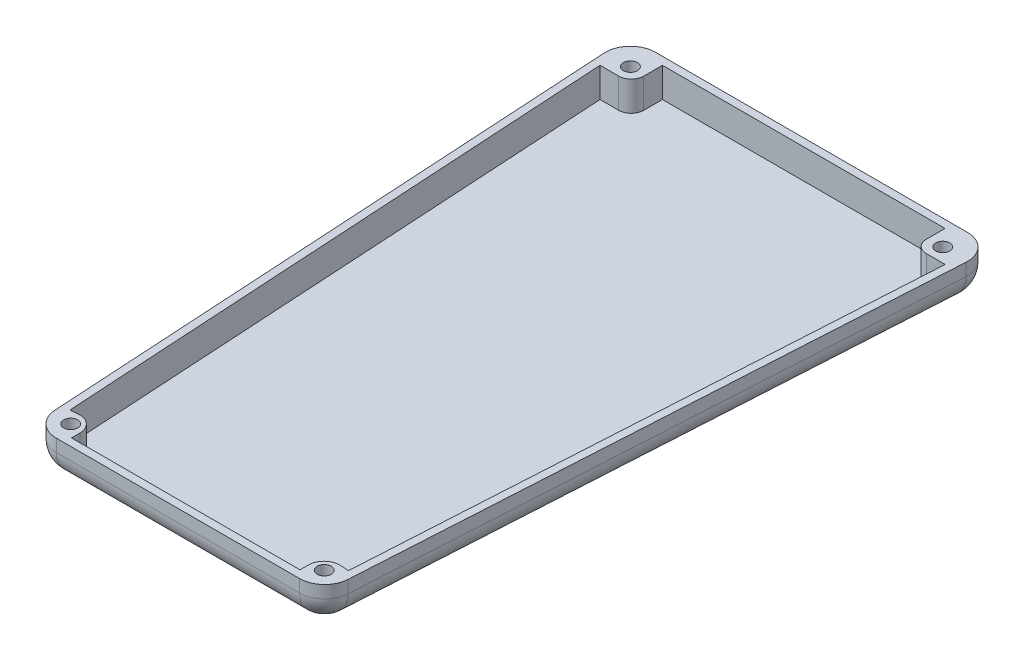
SolidWorks part; units mm, degrees
ref_plane "Front Plane" through (0, 0, 0) normal (0, 0, 1) x (1, 0, 0)
ref_plane "Top Plane" through (0, 0, 0) normal (0, 1, 0) x (1, 0, 0)
ref_plane "Right Plane" through (0, 0, 0) normal (1, 0, 0) x (0, 0, -1)
sketch "Sketch1" plane through (0, 76.7242, 0) normal (0, -1, 0) x (1, 0, 0)
  line L8 (110.2591, 82.3461) -> (10.2328, 82.3461) construction
  line L9 (110.2591, 82.3461) -> (10.2328, 82.3461)
  line L10 (21.3417, 285.3461) -> (99.2596, 285.3461) construction
  line L11 (2.2469, 90.8205) -> (13.3558, 277.8205) construction
  line L12 (107.2458, 277.8159) -> (118.2453, 90.8159) construction
  line L13 (21.3417, 285.3461) -> (99.2596, 285.3461)
  line L14 (2.2469, 90.8205) -> (13.3558, 277.8205)
  line L15 (107.2458, 277.8159) -> (118.2453, 90.8159)
  arc A0 (110.2591, 82.3461) -> (118.2453, 90.8159) centre (110.2591, 90.3461) ccw construction
  arc A1 (2.2469, 90.8205) -> (10.2328, 82.3461) centre (10.2328, 90.3461) ccw construction
  arc A2 (110.2591, 82.3461) -> (118.2453, 90.8159) centre (110.2591, 90.3461) ccw
  arc A3 (2.2469, 90.8205) -> (10.2328, 82.3461) centre (10.2328, 90.3461) ccw
  arc A4 (21.3417, 285.3461) -> (13.3558, 277.8205) centre (21.3417, 277.3461) ccw construction
  arc A5 (107.2458, 277.8159) -> (99.2596, 285.3461) centre (99.2596, 277.3461) ccw construction
  arc A6 (21.3417, 285.3461) -> (13.3558, 277.8205) centre (21.3417, 277.3461) ccw
  arc A7 (107.2458, 277.8159) -> (99.2596, 285.3461) centre (99.2596, 277.3461) ccw
extrude "Boss-Extrude1" add sketch "Sketch1" along normal blind 12
shell "Shell1" thickness 2.5
fillet "Fillet2" radius 8 8 edges at (116.0796, 64.7242, 84.8579) (60.2459, 64.7242, 82.3461) (4.4106, 64.7242, 84.8596) (7.8013, 64.7242, 184.3205) (15.8552, 64.7242, 283.1683) (60.3007, 64.7242, 285.3461) (104.7479, 64.7242, 283.1667) (112.7455, 64.7242, 184.3159)
sketch "Sketch5" plane through (0, 76.7242, 0) normal (0, 1, 0) x (1, 0, 0)
  line L0 (102.1959, -275.1575) -> (104.8885, -275.3159) construction
  line L1 (102.1959, -275.1575) -> (104.8885, -275.3159)
  line L2 (96.9023, -282.8461) -> (96.9023, -280.1489) construction
  line L3 (96.9023, -282.8461) -> (96.9023, -280.1489)
  line L4 (15.7117, -275.3205) -> (18.4011, -275.1608) construction
  line L5 (15.7117, -275.3205) -> (18.4011, -275.1608)
  line L6 (23.6976, -280.152) -> (23.6976, -282.8461) construction
  line L7 (23.6976, -280.152) -> (23.6976, -282.8461)
  line L8 (104.8885, -275.3159) -> (104.7501, -277.6691)
  line L9 (96.9023, -282.8461) -> (99.2596, -282.8461)
  line L10 (15.7117, -275.3205) -> (15.8514, -277.6723)
  line L11 (21.3417, -282.8461) -> (23.6976, -282.8461)
  line L12 (10.2328, -84.8461) -> (14.9904, -84.8461)
  line L13 (10.2328, -84.8461) -> (110.2591, -84.8461) construction
  line L14 (4.7425, -90.6723) -> (4.9904, -94.8461)
  line L15 (15.8514, -277.6723) -> (4.7425, -90.6723) construction
  line L16 (4.9904, -94.8461) -> (14.9904, -94.8461)
  line L17 (14.9904, -94.8461) -> (14.9904, -84.8461)
  line L18 (60.2459, -84.8461) -> (60.3007, -282.8461) construction
  line L19 (99.2596, -282.8461) -> (21.3417, -282.8461) construction
  line L20 (105.507, -94.8211) -> (105.5014, -84.8211)
  line L21 (115.507, -94.8156) -> (105.507, -94.8211)
  line L22 (115.7526, -90.6416) -> (115.507, -94.8156)
  line L23 (110.2591, -84.8185) -> (105.5014, -84.8211)
  arc A0 (102.1959, -275.1575) -> (96.9023, -280.1489) centre (101.9023, -280.1489) ccw construction
  arc A1 (102.1959, -275.1575) -> (96.9023, -280.1489) centre (101.9023, -280.1489) ccw
  arc A2 (23.6976, -280.152) -> (18.4011, -275.1608) centre (18.6976, -280.152) ccw construction
  arc A3 (23.6976, -280.152) -> (18.4011, -275.1608) centre (18.6976, -280.152) ccw
  circle A4 centre (10.2328, -90.3461) radius 1.5 construction
  circle A5 centre (10.2328, -90.3461) radius 1.5
  circle A6 centre (110.2591, -90.3461) radius 1.5 construction
  circle A7 centre (110.2591, -90.3461) radius 1.5
  circle A8 centre (100.9023, -279.0883) radius 1.5 construction
  circle A9 centre (100.9023, -279.0883) radius 1.5
  circle A10 centre (19.6976, -279.0908) radius 1.5 construction
  circle A11 centre (19.6976, -279.0908) radius 1.5
  arc A12 (99.2596, -282.8461) -> (104.7501, -277.6691) centre (99.2596, -277.3461) ccw construction
  arc A13 (99.2596, -282.8461) -> (104.7501, -277.6691) centre (99.2596, -277.3461) ccw
  arc A14 (15.8514, -277.6723) -> (21.3417, -282.8461) centre (21.3417, -277.3461) ccw construction
  arc A15 (15.8514, -277.6723) -> (21.3417, -282.8461) centre (21.3417, -277.3461) ccw
  arc A18 (10.2328, -84.8461) -> (4.7425, -90.6723) centre (10.2328, -90.3461) ccw construction
  arc A19 (10.2328, -84.8461) -> (4.7425, -90.6723) centre (10.2328, -90.3461) ccw
  arc A20 (110.2591, -84.8185) -> (115.7526, -90.6416) centre (110.2621, -90.3185) cw
  circle A21 centre (110.2621, -90.3185) radius 1.5
  line M6 (15.8514, -277.6723) -> (4.7425, -90.6723)
  line M9 (10.2328, -84.8461) -> (110.2591, -84.8461)
  arc M20 (4.7425, -90.6723) -> (10.2328, -84.8461) centre (10.2328, -90.3461) cw
  dimension "D1" = 10
  dimension "D2" = 10
extrude "Boss-Extrude3" add sketch "Sketch5" against normal up to surface (9.5 mm away) contours L16 L17 A5 M9 M20 M6 | A20 L22 L21 L20 L23 | A7 | A3 L5 L10 A15 L11 L7 | A11 | A1 L3 L9 A13 L8 L1 | A9
fillet "Fillet5" radius 4 2 edges at (14.9904, 71.9742, 94.8461) (105.507, 71.9742, 94.8211)
hole_wizard "CSK for M4 Countersunk Flat Head Screw1" positions "Sketch11" profile "Sketch12" countersink size "M4" standard "ISO"
sketch "Sketch11" plane through (0, 64.7242, 0) normal (0, -1, 0) x (-1, 0, 0)
  point P0 (-10.2328, -90.3461)
  point P3 (-110.2591, -90.3461)
sketch "Sketch12" plane through (10.2328, 64.7242, 90.3461) normal (1, 0, 0) x (0, 0, -1)
  line L0 (0, 0) -> (0, 13.3509)
  line L1 (0, 13.3509) -> (2.25, 11.999)
  line L2 (2.25, 11.999) -> (2.25, 2.45)
  line L3 (2.25, 2.45) -> (4.7, 0)
  line L5 (4.7, 0) -> (0, 0)
  line L6 (-2.25, 2.45) -> (-4.7, 0) construction
  line L10 (0, 13.3509) -> (-2.25, 11.999) construction
  line L11 (0, -6.35) -> (0, 107.95) construction
  dimension "Hole Dia." = 4.5
  dimension "Hole Depth" = 11.999
  dimension "Near C'Sink Dia." = 9.4
  dimension "Near C'Sink Angle" = 90
  dimension "Drill Angle" = 118
sketch "Sketch13" plane through (0, 64.7242, 0) normal (0, -1, 0) x (1, 0, 0)
  circle A0 centre (19.6976, 279.0908) radius 1.5 construction
  circle A1 centre (19.6976, 279.0908) radius 1.5
  circle A2 centre (100.9023, 279.0883) radius 1.5 construction
  circle A3 centre (100.9023, 279.0883) radius 1.5
hole_wizard "CSK for M4 Countersunk Flat Head Screw2" positions "Sketch14" profile "Sketch15" countersink size "M4" standard "ISO"
sketch "Sketch14" plane through (0, 64.7242, 0) normal (0, -1, 0) x (-1, 0, 0)
  point P0 (-100.9023, -279.0883)
  point P3 (-19.6976, -279.0908)
sketch "Sketch15" plane through (100.9023, 64.7242, 279.0883) normal (1, 0, 0) x (0, 0, -1)
  line L0 (0, 0) -> (0, 13.3509)
  line L1 (0, 13.3509) -> (2.25, 11.999)
  line L2 (2.25, 11.999) -> (2.25, 2.45)
  line L3 (2.25, 2.45) -> (4.7, 0)
  line L5 (4.7, 0) -> (0, 0)
  line L6 (-2.25, 2.45) -> (-4.7, 0) construction
  line L10 (0, 13.3509) -> (-2.25, 11.999) construction
  line L11 (0, -6.35) -> (0, 107.95) construction
  dimension "Hole Dia." = 4.5
  dimension "Hole Depth" = 11.999
  dimension "Near C'Sink Dia." = 9.4
  dimension "Near C'Sink Angle" = 90
  dimension "Drill Angle" = 118
